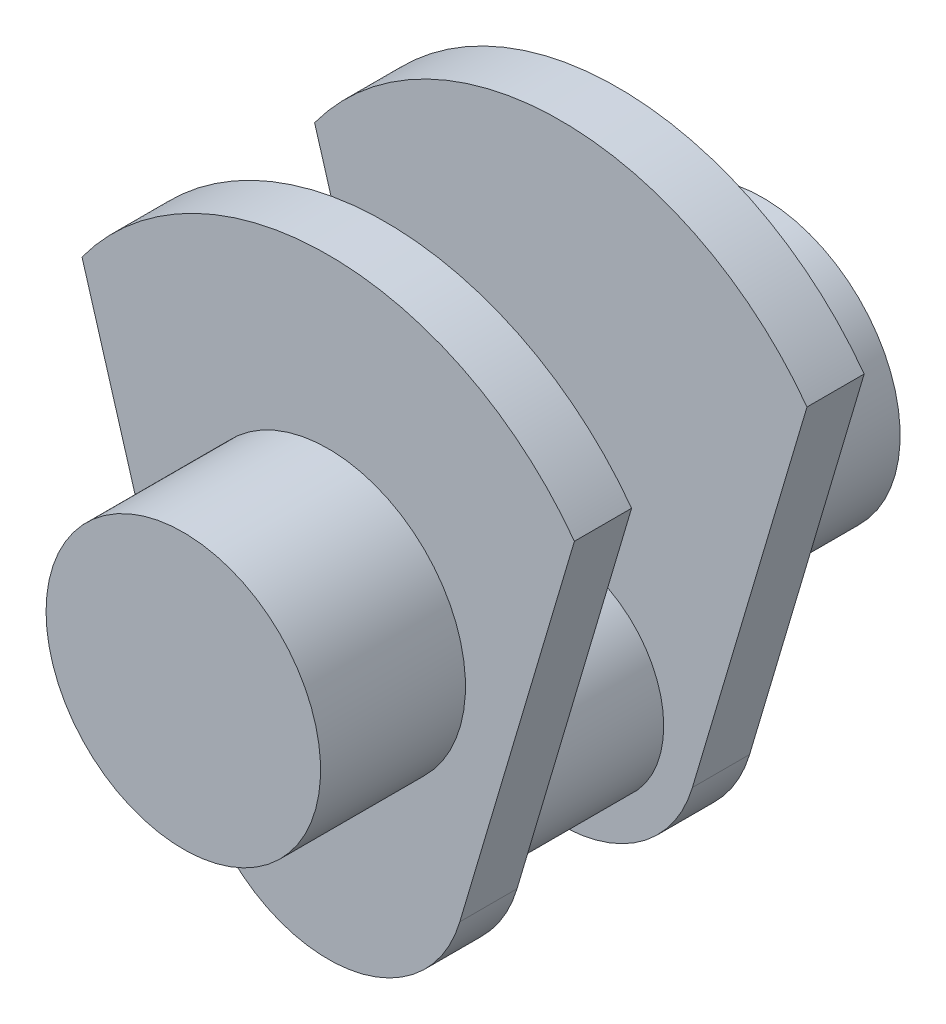
SolidWorks part; units mm, degrees
ref_plane "Front Plane" through (0, 0, 0) normal (0, 0, 1) x (1, 0, 0)
ref_plane "Top Plane" through (0, 0, 0) normal (0, 1, 0) x (1, 0, 0)
ref_plane "Right Plane" through (0, 0, 0) normal (1, 0, 0) x (0, 0, -1)
sketch "Sketch1" plane through (0, 0, 0) normal (0, 0, 1) x (1, 0, 0)
  line L0 (0, 78.5891) -> (0, -44) construction
  line L1 (-66.8459, 0) -> (117.8837, 0) construction
  line L2 (-34.5175, -54.2246) -> (-64.5699, 47.2306)
  line L3 (34.5175, -54.2246) -> (64.5699, 47.2306)
  circle A0 centre (0, -44) radius 36
  arc A1 (-64.5699, 47.2306) -> (64.5699, 47.2306) centre (0, 0) cw
  point P12 (73.4365, 33.8302)
  dimension "D1" = 72
  dimension "D3" = 80
  dimension "D2" = 33
  dimension "D4" = 44
extrude "Boss-Extrude1" add sketch "Sketch1" along normal blind 15 contours A1 L2 A0 L3 | A0
sketch "Sketch2" plane through (0, 0, 15) normal (0, 0, 1) x (1, 0, 0)
  circle A0 centre (0, -44) radius 27
  dimension "D1" = 54
extrude "Boss-Extrude2" add sketch "Sketch2" along normal blind 46
sketch "Sketch3" plane through (0, 0, 0) normal (0, 0, -1) x (-1, 0, 0)
  circle A0 centre (0, 0) radius 36
  dimension "D1" = 72
extrude "Boss-Extrude3" add sketch "Sketch3" along normal blind 38
ref_plane "Plane1" through (0, 0, 38) normal (0, 0, 1) x (1, 0, 0)
mirror "Mirror1" about plane through (0, 0, 38) normal (0, 0, 1) of bodies 103
